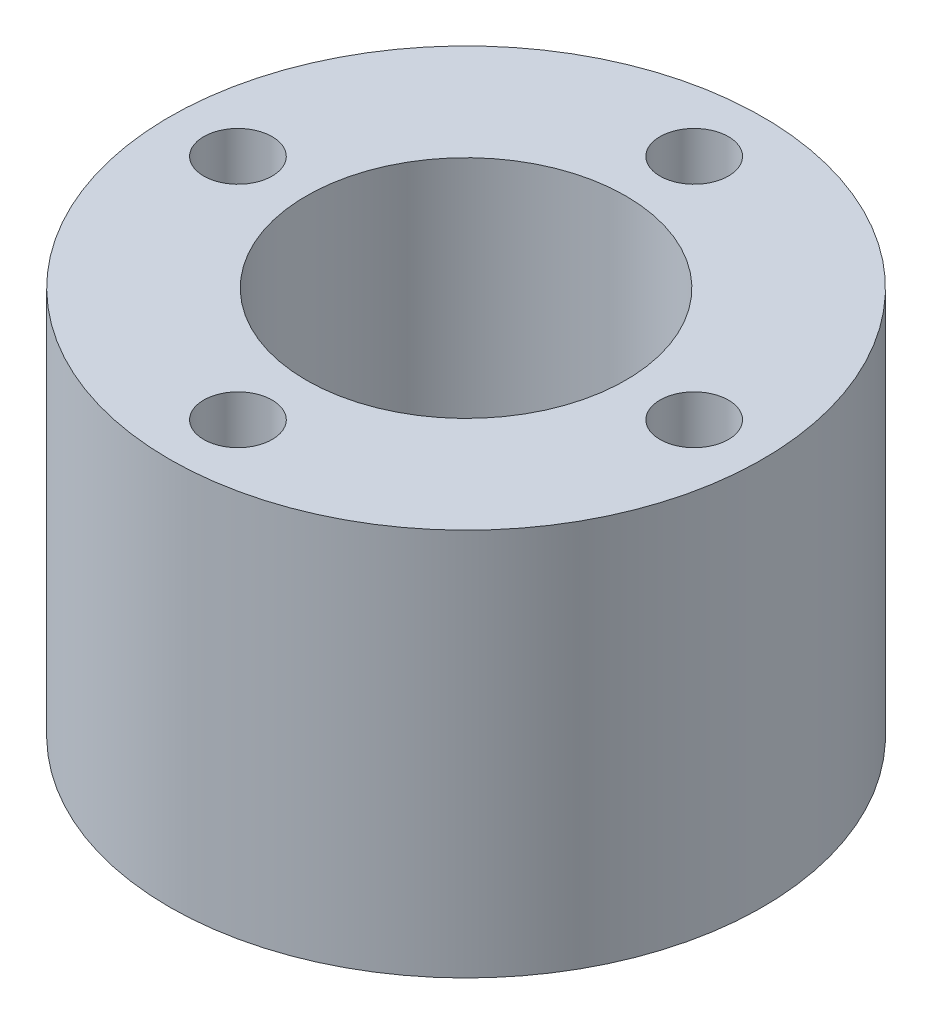
SolidWorks part; units mm, degrees
ref_plane "前视基准面" through (0, 0, 0) normal (0, 0, 1) x (1, 0, 0)
ref_plane "上视基准面" through (0, 0, 0) normal (0, 1, 0) x (1, 0, 0)
ref_plane "右视基准面" through (0, 0, 0) normal (1, 0, 0) x (0, 0, -1)
sketch "草图1" plane through (0, 0, 0) normal (0, 1, 0) x (1, 0, 0)
  line L0 (0, 10) -> (0, 7) construction
  circle A0 centre (0, 0) radius 13
  circle A1 centre (0, 0) radius 7
  circle A2 centre (0, 10) radius 1.5
  circle A3 centre (10, 0) radius 1.5
  circle A4 centre (0, -10) radius 1.5
  circle A5 centre (-10, 0) radius 1.5
  point P9 (0, 0)
  point P14 (0, 0)
  dimension "D1" = 26
  dimension "D2" = 14
  dimension "D3" = 3
  dimension "D4" = 3
  dimension "D5" = 4
extrude "凸台-拉伸1" add sketch "草图1" along normal blind 17
